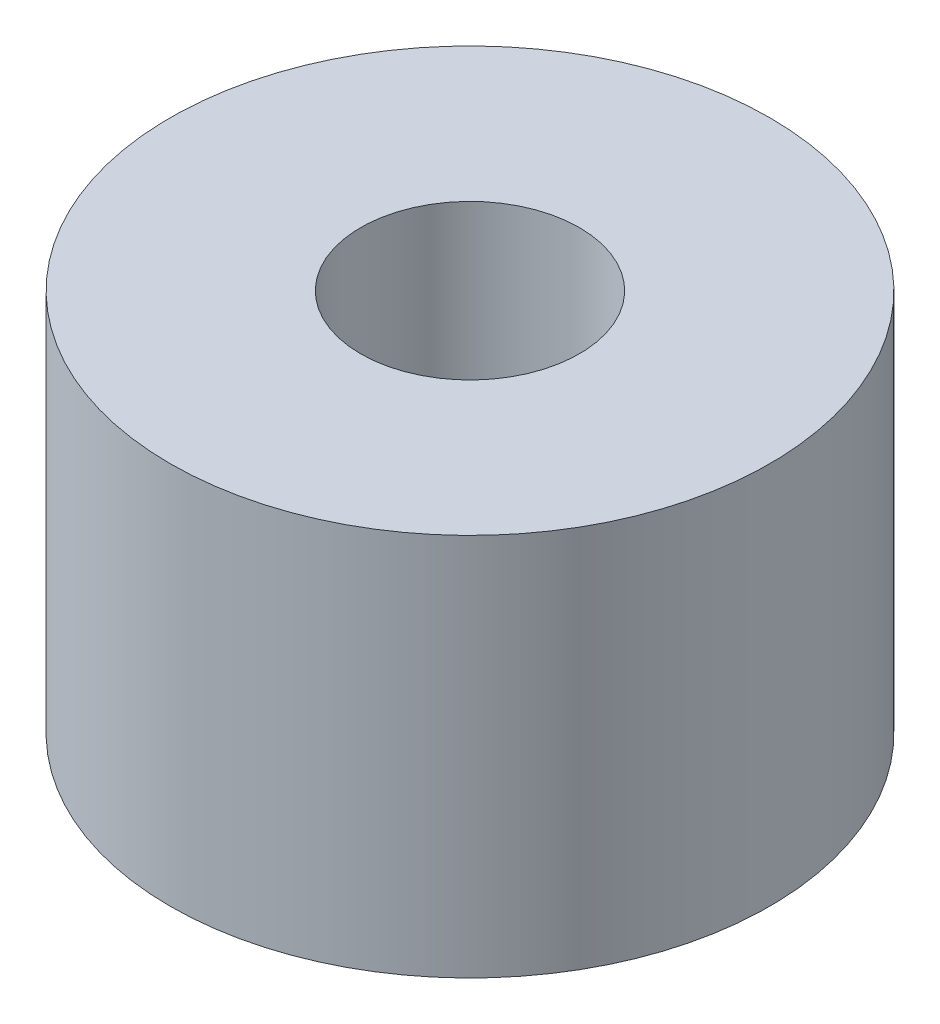
SolidWorks part; units mm, degrees
ref_plane "Front Plane" through (0, 0, 0) normal (0, 0, 1) x (1, 0, 0)
ref_plane "Top Plane" through (0, 0, 0) normal (0, 1, 0) x (1, 0, 0)
ref_plane "Right Plane" through (0, 0, 0) normal (1, 0, 0) x (0, 0, -1)
sketch "Sketch1" plane through (0, 0, 0) normal (0, 1, 0) x (1, 0, 0)
  circle A0 centre (0, 0) radius 3.175
  circle A1 centre (0, 0) radius 8.6995
  dimension "D1" = 17.399
extrude "Boss-Extrude1" add sketch "Sketch1" along normal blind 11.1252
